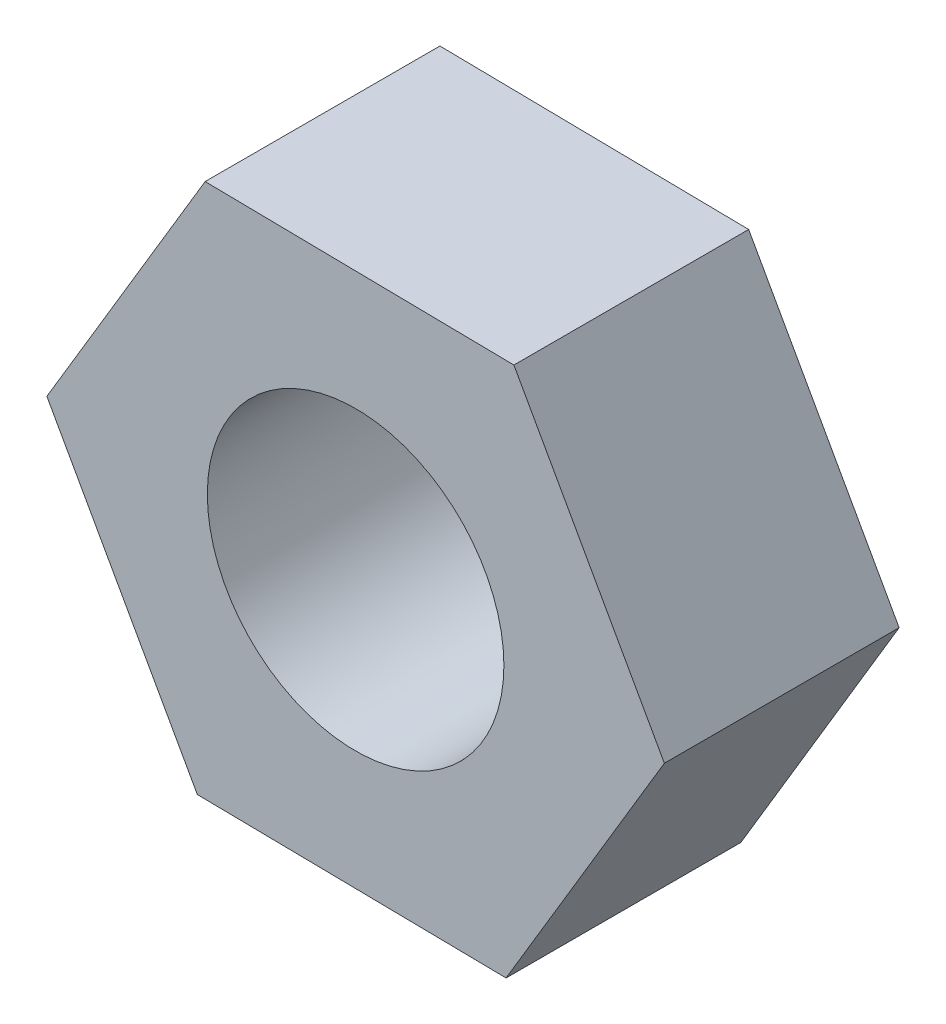
SolidWorks part; units mm, degrees
ref_plane "Front Plane" through (0, 0, 0) normal (0, 0, 1) x (1, 0, 0)
ref_plane "Top Plane" through (0, 0, 0) normal (0, 1, 0) x (1, 0, 0)
ref_plane "Right Plane" through (0, 0, 0) normal (1, 0, 0) x (0, 0, -1)
sketch "Sketch1" plane through (0, 0, 0) normal (0, 0, 1) x (1, 0, 0)
  line L1 (1.6012, 2.682) -> (-1.5221, 2.7276)
  line L2 (-1.5221, 2.7276) -> (-3.1232, 0.0457)
  line L3 (-3.1232, 0.0457) -> (-1.6012, -2.682)
  line L4 (-1.6012, -2.682) -> (1.5221, -2.7276)
  line L5 (1.5221, -2.7276) -> (3.1232, -0.0457)
  line L6 (3.1232, -0.0457) -> (1.6012, 2.682)
  circle A0 centre (0, 0) radius 2.7051 construction
  dimension "D1" = 5.4102
extrude "Boss-Extrude1" add sketch "Sketch1" along normal blind 2.3749
sketch "Sketch2" plane through (0, 0, 2.3749) normal (0, 0, 1) x (1, 0, 0)
  circle A0 centre (0, 0) radius 1.5
  dimension "D1" = 3
extrude "Cut-Extrude1" cut sketch "Sketch2" against normal blind 2.3749
